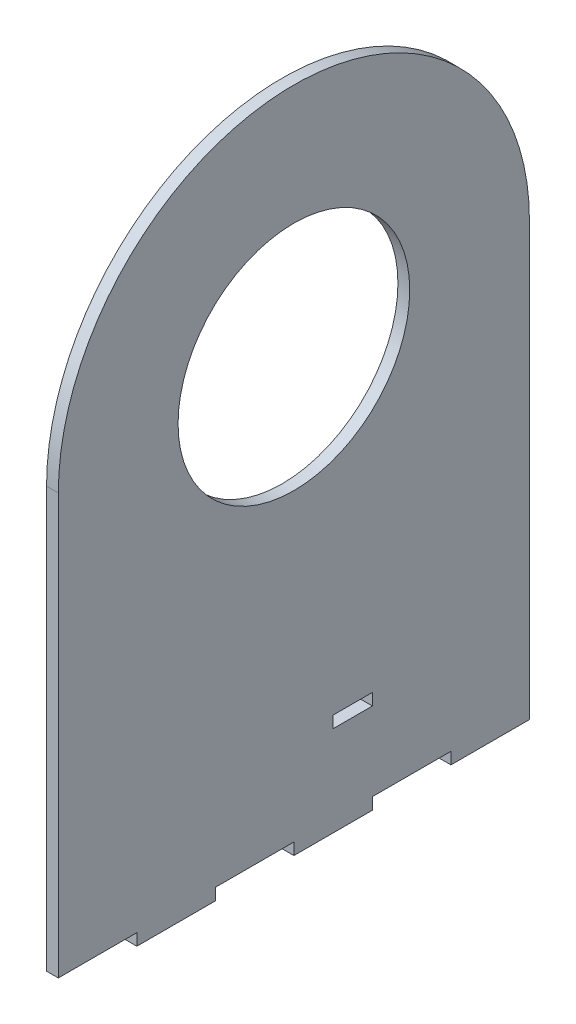
SolidWorks part; units mm, degrees
ref_plane "Alzado" through (0, 0, 0) normal (0, 0, 1) x (1, 0, 0)
ref_plane "Planta" through (0, 0, 0) normal (0, 1, 0) x (1, 0, 0)
ref_plane "Vista lateral" through (0, 0, 0) normal (1, 0, 0) x (0, 0, -1)
sketch "Croquis1" plane through (0, 0, 0) normal (1, 0, 0) x (0, 0, -1)
  line L0 (-60, -82) -> (-40, -82)
  line L1 (-20, -82) -> (0, -82)
  line L2 (60, -85) -> (60, 25)
  line L3 (-40, -82) -> (-40, -85)
  line L4 (-60, -82) -> (-60, 25)
  line L5 (60, -85) -> (-60, 85) construction
  line L6 (60, 85) -> (-60, -85) construction
  line L7 (-40, -85) -> (-20, -85)
  line L8 (-20, -85) -> (-20, -82)
  line L9 (0, -82) -> (0, -85)
  line L10 (0, -85) -> (20, -85)
  line L11 (20, -85) -> (20, -82)
  line L12 (20, -82) -> (40, -82)
  line L13 (40, -82) -> (40, -85)
  line L14 (40, -85) -> (60, -85)
  line L15 (60, -85) -> (60, -82)
  line L17 (20, -62) -> (10, -62)
  line L18 (20, -62) -> (20, -59)
  line L19 (20, -59) -> (10, -59)
  line L20 (10, -62) -> (10, -59)
  line L21 (20, -62) -> (10, -59) construction
  line L22 (20, -59) -> (10, -62) construction
  circle A0 centre (0, 25) radius 29.5
  arc A1 (60, 25) -> (-60, 25) centre (0, 25) ccw
  point P0 (0, 0)
  point P9 (15, -60.5)
  dimension "D3" = 107
  dimension "D4" = 60
  dimension "D1" = 3
  dimension "D2" = 120
  dimension "D5" = 40
  dimension "D6" = 20
extrude "Saliente-Extruir1" add sketch "Croquis1" along normal blind 3 contours L2 A1 L4 L0 L3 L7 L8 L1 L9 L10 L11 L12 L13 L14 A0
